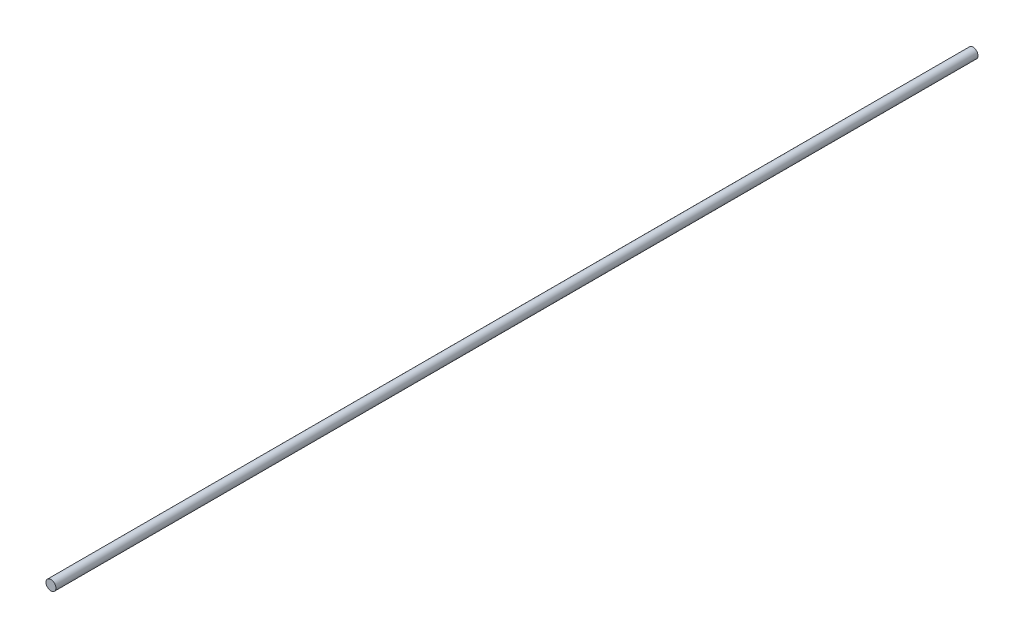
SolidWorks part; units mm, degrees
material "2014-T6"
ref_plane "Front Plane" through (0, 0, 0) normal (0, 0, 1) x (1, 0, 0)
ref_plane "Top Plane" through (0, 0, 0) normal (0, 1, 0) x (1, 0, 0)
ref_plane "Right Plane" through (0, 0, 0) normal (1, 0, 0) x (0, 0, -1)
sketch "Sketch1" plane through (0, 0, 0) normal (0, 0, 1) x (1, 0, 0)
  circle A0 centre (0, 0) radius 6.35
  dimension "D1" = 12.7
extrude "Boss-Extrude1" add sketch "Sketch1" against normal blind 1178.306 contours A0
equation "\"Dia\" = .5in"
equation "\"A\"= ( \"Dia\" ^ 2 * 3.14159 ) / 4"
equation "\"Df\"= .009in"
equation "\"E\"= 10500.73221"
equation "\"F\" = .4"
equation "\"L\"= ( \"Df\" * \"A\" * \"E\" ) / \"F\""
